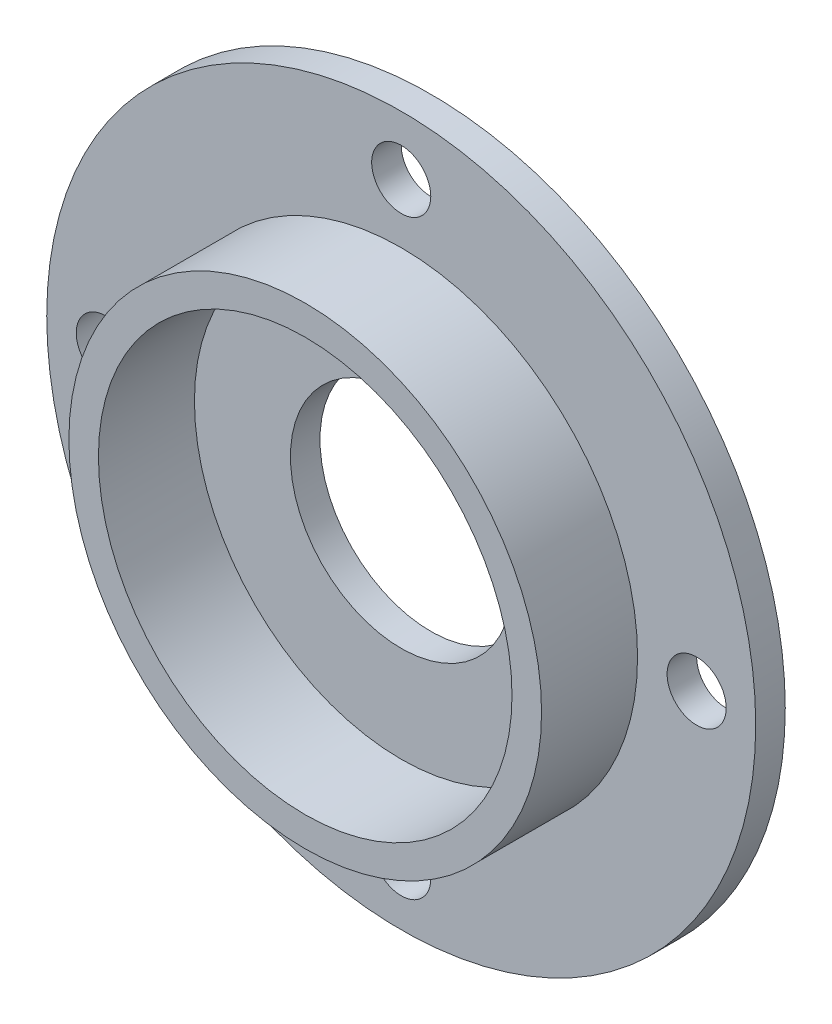
SolidWorks part; units mm, degrees
ref_plane "前视" through (0, 0, 0) normal (0, 0, 1) x (1, 0, 0)
ref_plane "上视" through (0, 0, 0) normal (0, 1, 0) x (1, 0, 0)
ref_plane "右视" through (0, 0, 0) normal (1, 0, 0) x (0, 0, -1)
sketch "草图1" plane through (0, 0, 0) normal (0, 0, 1) x (1, 0, 0)
  line L0 (0, 155.7418) -> (0, -151.0312) construction
  line L1 (155.2911, 0) -> (-154.426, 0) construction
  circle A0 centre (0, 0) radius 120
  circle A1 centre (0, 0) radius 37.5
  circle A2 centre (0, 0) radius 100 construction
  circle A3 centre (0, 100) radius 10
  circle A4 centre (100, 0) radius 10
  circle A5 centre (0, -100) radius 10
  circle A6 centre (-100, 0) radius 10
  dimension "D1" = 75
  dimension "D2" = 240
  dimension "D3" = 200
  dimension "D4" = 20
  dimension "D5" = 20
  dimension "D6" = 20
  dimension "D7" = 20
extrude "拉伸1" add sketch "草图1" along normal blind 10
sketch "草图2" plane through (0, 0, 10) normal (0, 0, 1) x (1, 0, 0)
  circle A0 centre (0, 0) radius 80
  circle A1 centre (0, 0) radius 70
  dimension "D1" = 140
  dimension "D2" = 160
extrude "拉伸2" add sketch "草图2" along normal blind 32.5
